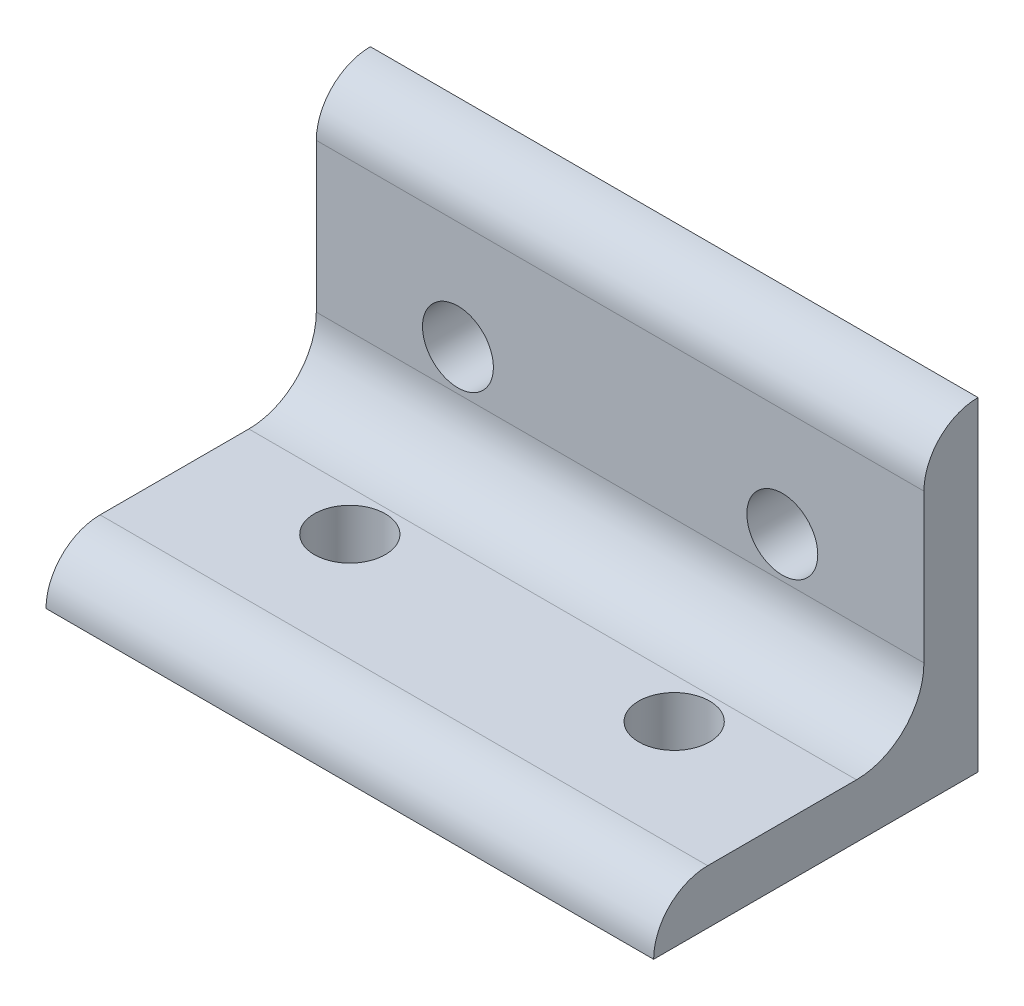
SolidWorks part; units mm, degrees
material "6063-T83"
ref_plane "Front Plane" through (0, 0, 0) normal (0, 0, 1) x (1, 0, 0)
ref_plane "Top Plane" through (0, 0, 0) normal (0, 1, 0) x (1, 0, 0)
ref_plane "Right Plane" through (0, 0, 0) normal (1, 0, 0) x (0, 0, -1)
ref_plane "Plane1" through (35.687, 0, 0) normal (1, 0, 0) x (0, 0, -1)
sketch "Sketch1" plane through (35.687, 0, 0) normal (1, 0, 0) x (0, 0, -1)
  line L0 (-38.1, 0) -> (0, 0)
  line L1 (0, 0) -> (0, 38.1)
  line L2 (-6.35, 31.75) -> (-6.35, 6.35)
  line L3 (-6.35, 6.35) -> (-31.75, 6.35)
  arc A0 (-31.75, 6.35) -> (-38.1, 0) centre (-31.75, 0) ccw
  arc A1 (0, 38.1) -> (-6.35, 31.75) centre (0, 31.75) ccw
extrude "Boss-Extrude1" add sketch "Sketch1" against normal blind 71.374
hole_wizard "Hole1" positions "Sketch3" profile "Sketch2" legacy
sketch "Sketch3" plane through (0, 0, 6.35) normal (0, 0, 1) x (1, 0, 0)
  point P0 (19.05, 19.05)
  point P1 (-19.05, 19.05)
sketch "Sketch2" plane through (19.05, 19.05, 6.35) normal (1, 0, 0) x (0, -1, 0)
  line L0 (0, 0) -> (0, 6.35)
  line L1 (0, 6.35) -> (4.1656, 6.35)
  line L2 (4.1656, 6.35) -> (4.1656, 0)
  line L3 (4.1656, 0) -> (0, 0)
  line L4 (0, 110) -> (0, -10) construction
  dimension "Diameter" = 8.3312
  dimension "Depth" = 6.35
hole_wizard "Hole2" positions "Sketch5" profile "Sketch4" legacy
sketch "Sketch5" plane through (0, 6.35, 0) normal (0, 1, 0) x (1, 0, 0)
  point P0 (19.05, -19.05)
  point P1 (-19.05, -19.05)
sketch "Sketch4" plane through (19.05, 6.35, 19.05) normal (1, 0, 0) x (0, 0, 1)
  line L0 (0, 0) -> (0, 6.35)
  line L1 (0, 6.35) -> (4.1656, 6.35)
  line L2 (4.1656, 6.35) -> (4.1656, 0)
  line L3 (4.1656, 0) -> (0, 0)
  line L4 (0, 110) -> (0, -10) construction
  dimension "Diameter" = 8.3312
  dimension "Depth" = 6.35
fillet "Fillet1" radius 7.9248 1 edges at (0, 6.35, 6.35)
